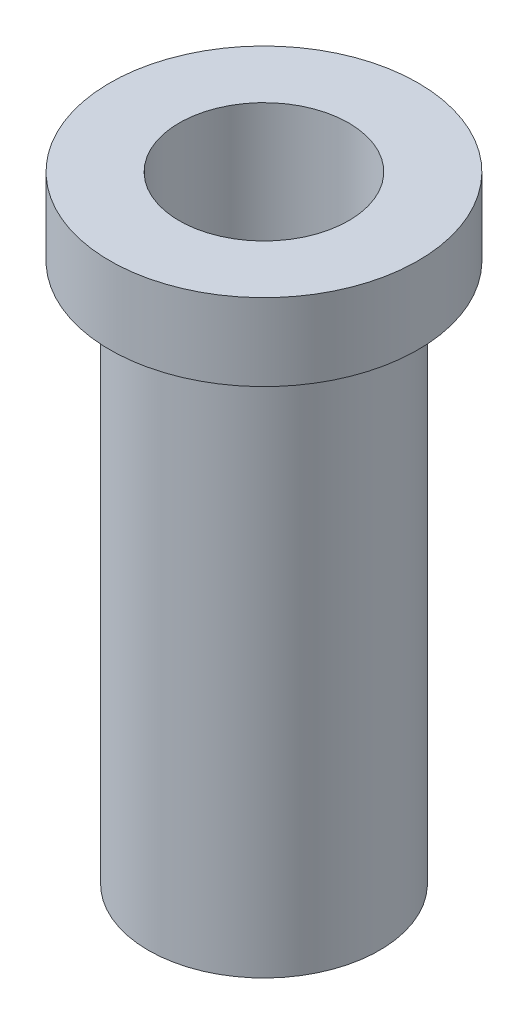
SolidWorks part; units mm, degrees
ref_plane "Front Plane" through (0, 0, 0) normal (0, 0, 1) x (1, 0, 0)
ref_plane "Top Plane" through (0, 0, 0) normal (0, 1, 0) x (1, 0, 0)
ref_plane "Right Plane" through (0, 0, 0) normal (1, 0, 0) x (0, 0, -1)
sketch "Sketch2" plane through (0, 0, 0) normal (0, 0, 1) x (1, 0, 0)
  line L0 (5.5, 0) -> (5.5, 40)
  line L1 (5.5, 40) -> (10, 40)
  line L2 (10, 40) -> (10, 35)
  line L3 (10, 35) -> (7.5, 35)
  line L4 (7.5, 35) -> (7.5, 0)
  line L5 (7.5, 0) -> (5.5, 0)
  line L6 (0, 0) -> (0, 30.4762) construction
  dimension "D1" = 5.5
  dimension "D2" = 7.5
  dimension "D3" = 10
  dimension "D4" = 40
  dimension "D5" = 5
revolve "Revolve1" add sketch "Sketch2" angle 360 about L6
